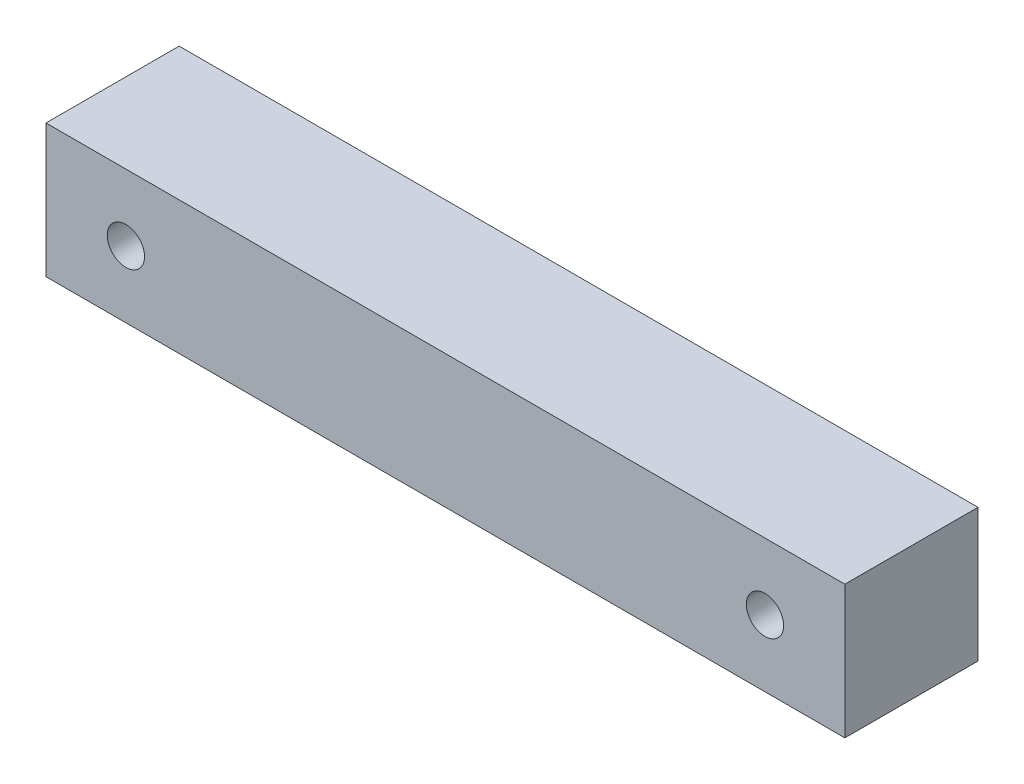
SolidWorks part; units mm, degrees
ref_plane "前视基准面" through (0, 0, 0) normal (0, 0, 1) x (1, 0, 0)
ref_plane "上视基准面" through (0, 0, 0) normal (0, 1, 0) x (1, 0, 0)
ref_plane "右视基准面" through (0, 0, 0) normal (1, 0, 0) x (0, 0, -1)
other "Configuration Table"
sketch "草图1" plane through (0, 0, 0) normal (0, 1, 0) x (1, 0, 0)
  line L1 (0, 0) -> (60, 0)
  line L2 (0, 0) -> (0, 10)
  line L3 (0, 10) -> (60, 10)
  line L4 (60, 0) -> (60, 10)
  dimension "D1" = 10
  dimension "D2" = 60
extrude "凸台-拉伸1" add sketch "草图1" along normal blind 10
sketch "草图3" plane through (0, 0, 0) normal (0, 0, 1) x (1, 0, 0)
  line L0 (0, 10) -> (0, 0) construction
  line L1 (60, 10) -> (60, 0) construction
  circle A0 centre (6, 5) radius 1.4
  circle A1 centre (54, 5) radius 1.4
  dimension "D1" = 2.8
  dimension "D2" = 6
  dimension "D3" = 2.8
  dimension "D4" = 6
extrude "切除-拉伸1" cut sketch "草图3" against normal blind 20
